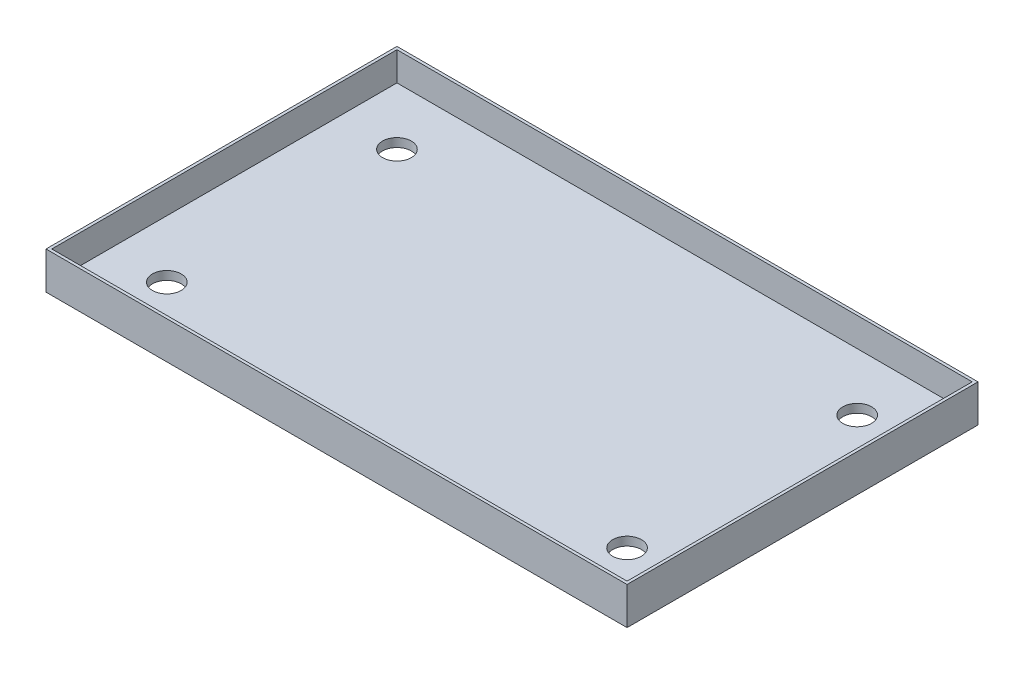
SolidWorks part; units mm, degrees
ref_plane "Front Plane" through (0, 0, 0) normal (0, 0, 1) x (1, 0, 0)
ref_plane "Top Plane" through (0, 0, 0) normal (0, 1, 0) x (1, 0, 0)
ref_plane "Right Plane" through (0, 0, 0) normal (1, 0, 0) x (0, 0, -1)
sketch "Sketch1" plane through (0, 0, 0) normal (0, 1, 0) x (1, 0, 0)
  line L0 (0, -55) -> (0, 55) construction
  line L1 (100, -60) -> (-100, -60)
  line L2 (100, -60) -> (100, 60)
  line L3 (100, 60) -> (-100, 60)
  line L4 (-100, -60) -> (-100, 60)
  line L5 (100, -60) -> (-100, 60) construction
  line L6 (100, 60) -> (-100, -60) construction
  line L7 (-55, 0) -> (55, 0) construction
  circle A0 centre (-80, 40) radius 5
  circle A1 centre (80, 40) radius 5
  circle A2 centre (80, -40) radius 5
  circle A3 centre (-80, -40) radius 5
  point P0 (0, 0)
  point P18 (0, 0)
  dimension "D3" = 10
  dimension "D1" = 200
  dimension "D2" = 120
  dimension "D4" = 20
  dimension "D5" = 20
extrude "Boss-Extrude3" add sketch "Sketch1" along normal mid plane 3
sketch "Sketch2" plane through (-100, 0, 0) normal (-1, 0, 0) x (0, 0, 1)
  line L0 (0, 17.261) -> (0, -11.6439) construction
  line L2 (-60, -1.5) -> (60, -1.5)
  line L3 (-60, -1.5) -> (-60, 11.5)
  line L4 (-60, 11.5) -> (60, 11.5)
  line L5 (60, -1.5) -> (60, 11.5)
  dimension "D1" = 120
  dimension "D2" = 13
extrude "Boss-Extrude4" add sketch "Sketch2" along normal blind 1
mirror "Mirror1" about plane through (0, 0, 0) normal (1, 0, 0) of "Boss-Extrude4"
sketch "Sketch3" plane through (0, 0, -60) normal (0, 0, -1) x (-1, 0, 0)
  line L5 (-101, -1.5) -> (101, -1.5)
  line L6 (-101, -1.5) -> (-101, 11.5)
  line L7 (-101, 11.5) -> (101, 11.5)
  line L8 (101, -1.5) -> (101, 11.5)
extrude "Boss-Extrude6" add sketch "Sketch3" along normal blind 1
mirror "Mirror2" about plane through (0, 0, 0) normal (0, 0, 1) of "Boss-Extrude6"
